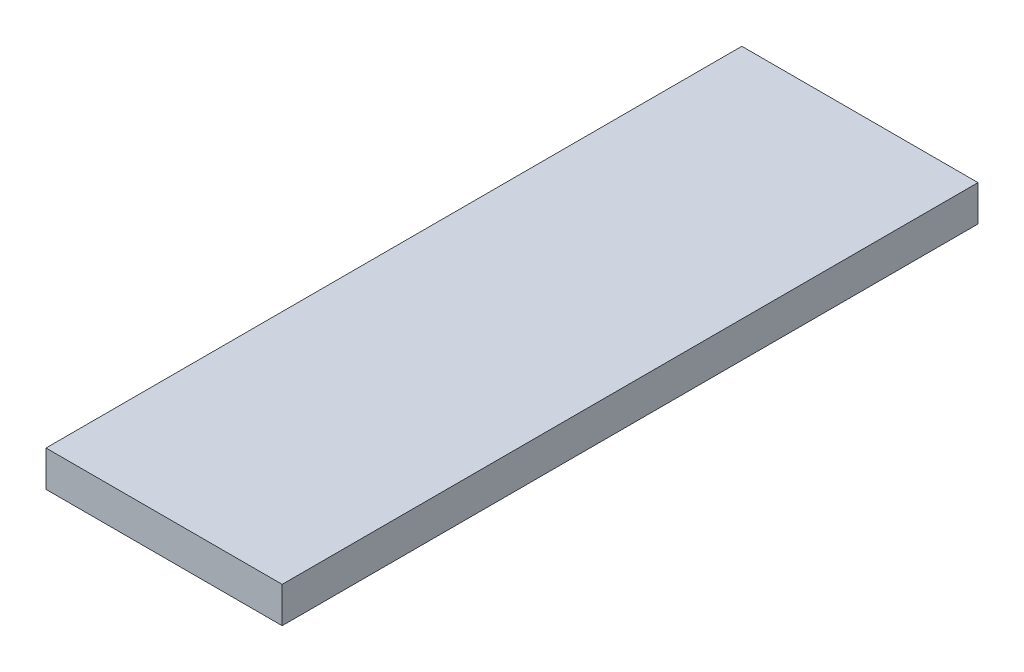
SolidWorks part; units mm, degrees
material "ABS"
ref_plane "Front Plane" through (0, 0, 0) normal (0, 0, 1) x (1, 0, 0)
ref_plane "Top Plane" through (0, 0, 0) normal (0, 1, 0) x (1, 0, 0)
ref_plane "Right Plane" through (0, 0, 0) normal (1, 0, 0) x (0, 0, -1)
sketch "Sketch1" plane through (0, 0, 0) normal (0, 1, 0) x (1, 0, 0)
  line L1 (-28, -82.5) -> (28, -82.5)
  line L2 (-28, -82.5) -> (-28, 82.5)
  line L3 (-28, 82.5) -> (28, 82.5)
  line L4 (28, -82.5) -> (28, 82.5)
  line L5 (-28, -82.5) -> (28, 82.5) construction
  line L6 (-28, 82.5) -> (28, -82.5) construction
  point P0 (0, 0)
  dimension "D1" = 56
  dimension "D2" = 165
extrude "Boss-Extrude1" add sketch "Sketch1" along normal mid plane 8.5
